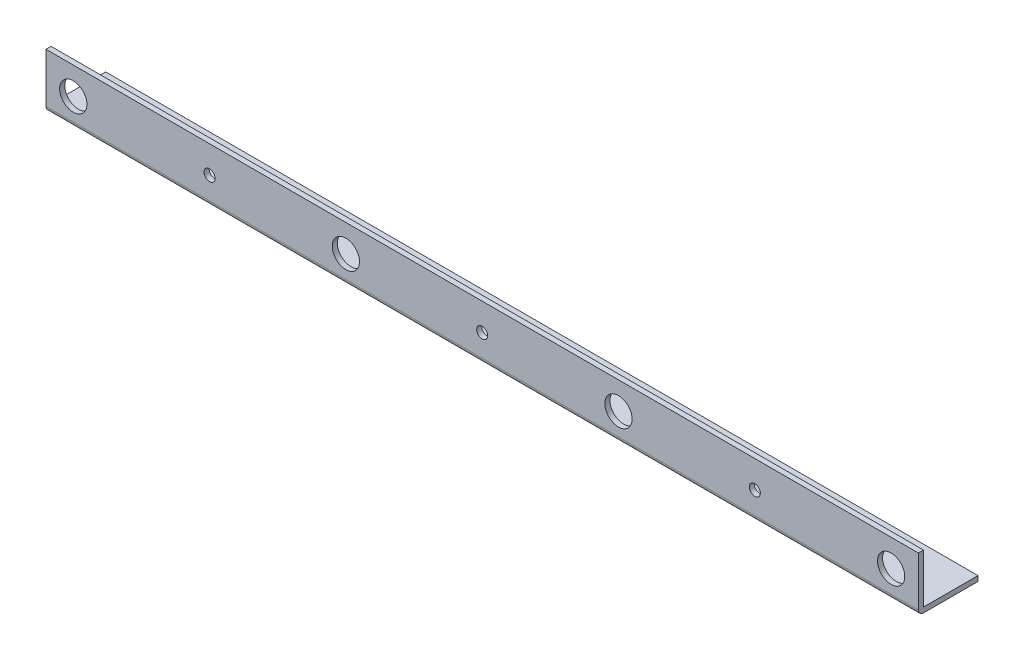
SolidWorks part; units mm, degrees
ref_plane "Front Plane" through (0, 0, 0) normal (0, 0, 1) x (1, 0, 0)
ref_plane "Top Plane" through (0, 0, 0) normal (0, 1, 0) x (1, 0, 0)
ref_plane "Right Plane" through (0, 0, 0) normal (1, 0, 0) x (0, 0, -1)
sketch "Sketch1" plane through (0, 0, 0) normal (0, 1, 0) x (1, 0, 0)
  line L1 (0, 0) -> (406.4, 0)
  line L2 (0, 0) -> (0, 25.4)
  line L3 (0, 25.4) -> (406.4, 25.4)
  line L4 (406.4, 0) -> (406.4, 25.4)
  dimension "D1" = 25.4
  dimension "D2" = 406.4
extrude "Boss-Extrude1" add sketch "Sketch1" along normal blind 2.3813
sketch "Sketch2" plane through (0, 0, 0) normal (0, 0, 1) x (1, 0, 0)
  line L0 (0, 0) -> (406.4, 0) construction
  line L1 (0, 0) -> (406.4, 0)
  line L2 (0, 0) -> (0, 25.4)
  line L3 (0, 25.4) -> (406.4, 25.4)
  line L4 (406.4, 0) -> (406.4, 25.4)
  line L5 (12.7, 12.7) -> (139.7, 12.7) construction
  line L6 (139.7, 12.7) -> (266.7, 12.7) construction
  line L7 (266.7, 12.7) -> (393.7, 12.7) construction
  circle A0 centre (12.7, 12.7) radius 6.35
  circle A1 centre (139.7, 12.7) radius 6.35
  circle A2 centre (266.7, 12.7) radius 6.35
  circle A3 centre (393.7, 12.7) radius 6.35
  circle A4 centre (76.2, 12.7) radius 2.5797
  circle A5 centre (203.2, 12.7) radius 2.5797
  circle A6 centre (330.2, 12.7) radius 2.5797
  dimension "D2" = 12.7
  dimension "D5" = 12.7
  dimension "D6" = 5.1594
  dimension "D1" = 25.4
  dimension "D3" = 12.7
  dimension "D4" = 12.7
extrude "Boss-Extrude2" add sketch "Sketch2" along normal blind 2.3813
fillet "Fillet1" radius 2.3813 1 edges at (203.2, 0, 2.3813)
